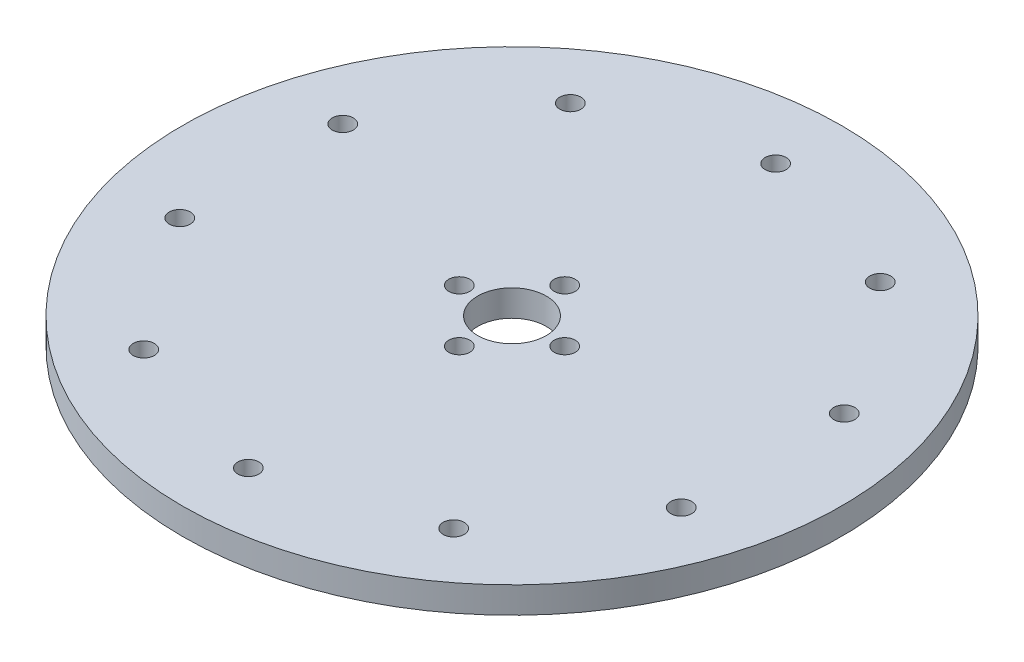
SolidWorks part; units mm, degrees
ref_plane "前视基准面" through (0, 0, 0) normal (0, 0, 1) x (1, 0, 0)
ref_plane "上视基准面" through (0, 0, 0) normal (0, 1, 0) x (1, 0, 0)
ref_plane "右视基准面" through (0, 0, 0) normal (1, 0, 0) x (0, 0, -1)
sketch "草图1" plane through (0, 0, 0) normal (0, 1, 0) x (1, 0, 0)
  circle A0 centre (0, 0) radius 50
extrude "凸台-拉伸1" add sketch "草图1" along normal blind 4
sketch "草图2" plane through (0, 4, 0) normal (0, 1, 0) x (1, 0, 0)
  circle A0 centre (0, 0) radius 8
  circle A1 centre (0, 8) radius 1.6
  circle A2 centre (8, 0) radius 1.6
  circle A3 centre (0, -8) radius 1.6
  circle A4 centre (-8, 0) radius 1.6
  circle A5 centre (0, 0) radius 5.2
extrude "切除-拉伸1" cut sketch "草图2" against normal blind 4 contours A0 A4 | A0 A4 | A0 A1 | A0 A1 | A0 A2 | A0 A2 | A0 A3 | A0 A3 | A5
sketch "草图3" plane through (0, 4, 0) normal (0, 1, 0) x (1, 0, 0)
  circle A3 centre (0, 40) radius 1.6
  circle A4 centre (23.5114, 32.3607) radius 1.6
  circle A5 centre (38.0423, 12.3607) radius 1.6
  circle A6 centre (38.0423, -12.3607) radius 1.6
  circle A7 centre (23.5114, -32.3607) radius 1.6
  circle A8 centre (0, -40) radius 1.6
  circle A9 centre (-23.5114, -32.3607) radius 1.6
  circle A10 centre (-38.0423, -12.3607) radius 1.6
  circle A11 centre (-38.0423, 12.3607) radius 1.6
  circle A12 centre (-23.5114, 32.3607) radius 1.6
extrude "切除-拉伸2" cut sketch "草图3" against normal blind 10
